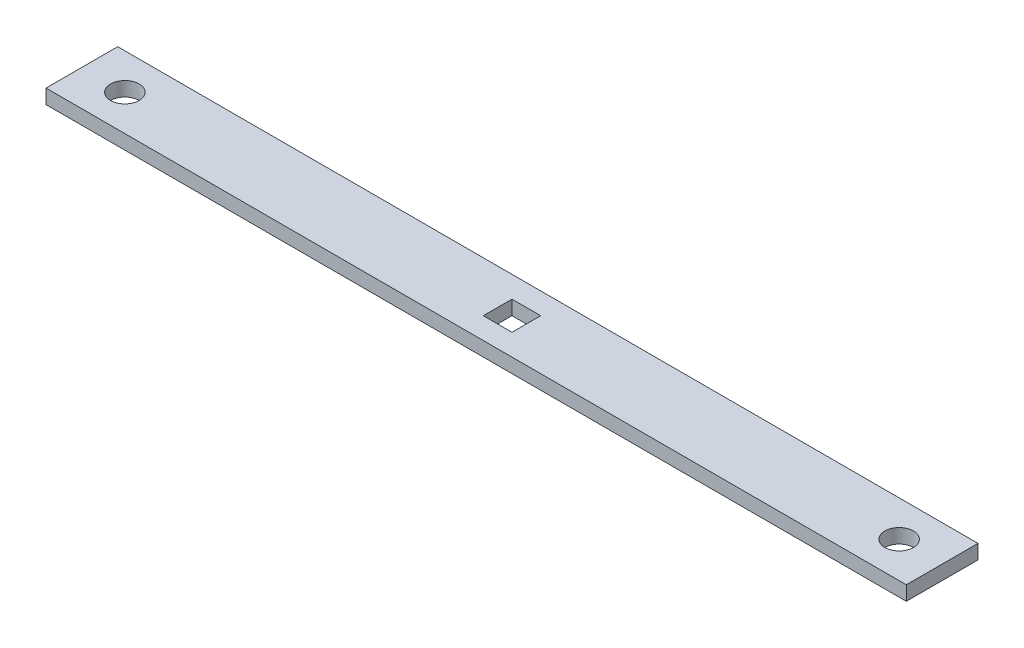
SolidWorks part; units mm, degrees
ref_plane "Front Plane" through (0, 0, 0) normal (0, 0, 1) x (1, 0, 0)
ref_plane "Top Plane" through (0, 0, 0) normal (0, 1, 0) x (1, 0, 0)
ref_plane "Right Plane" through (0, 0, 0) normal (1, 0, 0) x (0, 0, -1)
sketch "Sketch2" plane through (0, 0, 0) normal (0, 1, 0) x (1, 0, 0)
  line L1 (-15, -1.25) -> (15, -1.25)
  line L2 (-15, -1.25) -> (-15, 1.25)
  line L3 (-15, 1.25) -> (15, 1.25)
  line L4 (15, -1.25) -> (15, 1.25)
  line L5 (-15, -1.25) -> (15, 1.25) construction
  line L6 (-15, 1.25) -> (15, -1.25) construction
  point P0 (0, 0)
  dimension "D1" = 2.5
  dimension "D2" = 30
extrude "Boss-Extrude1" add sketch "Sketch2" along normal blind 0.5
sketch "Sketch3" plane through (0, 0.5, 0) normal (0, 1, 0) x (1, 0, 0)
  line L1 (-0.5, -0.5) -> (0.5, -0.5)
  line L2 (-0.5, -0.5) -> (-0.5, 0.5)
  line L3 (-0.5, 0.5) -> (0.5, 0.5)
  line L4 (0.5, -0.5) -> (0.5, 0.5)
  line L5 (-0.5, -0.5) -> (0.5, 0.5) construction
  line L6 (-0.5, 0.5) -> (0.5, -0.5) construction
  circle A0 centre (-13.5, 0) radius 0.5
  circle A1 centre (13.5, 0) radius 0.5
  point P4 (0, 0)
  dimension "D1" = 1
  dimension "D4" = 1
  dimension "D2" = 13.5
  dimension "D3" = 13.5
  dimension "D5" = 1
extrude "Cut-Extrude1" cut sketch "Sketch3" against normal through all both and the other way through all
